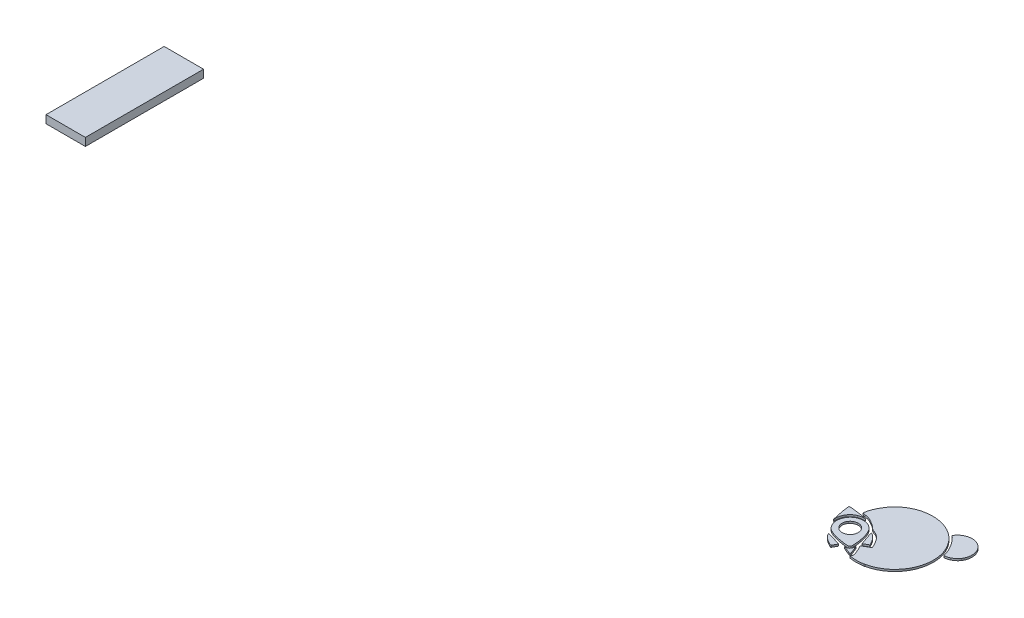
SolidWorks part; units mm, degrees
ref_plane "Alzado" through (0, 0, 0) normal (0, 0, 1) x (1, 0, 0)
ref_plane "Planta" through (0, 0, 0) normal (0, 1, 0) x (1, 0, 0)
ref_plane "Vista lateral" through (0, 0, 0) normal (1, 0, 0) x (0, 0, -1)
sketch "Croquis2" plane through (0, 0, 0) normal (0, 1, 0) x (1, 0, 0)
  line L1 (-10.1434, 10.8277) -> (39.8566, 10.8277)
  line L2 (-10.1434, 10.8277) -> (-10.1434, -4.1723)
  line L3 (-10.1434, -4.1723) -> (39.8566, -4.1723)
  line L4 (39.8566, 10.8277) -> (39.8566, -4.1723)
  line L5 (-10.1434, 10.8277) -> (39.8566, -4.1723) construction
  line L6 (-10.1434, -4.1723) -> (39.8566, 10.8277) construction
  point P0 (14.8566, 3.3277)
  dimension "D1" = 50
  dimension "D2" = 15
sketch "Croquis1" plane through (0, 0, 0) normal (0, 1, 0) x (1, 0, 0)
  line L0 (3.5784, 3.9291) -> (1.8314, 3.9291)
  line L1 (3.9335, 5.4773) -> (5.155, 5.4773)
  line L2 (5.155, 5.4773) -> (5.155, 2.4804)
  line L3 (5.155, 2.4804) -> (5.1692, 2.4804)
  line L4 (3.0387, 4.4262) -> (4.0755, 4.4262)
  line L5 (4.0755, 4.4262) -> (4.0755, -0.829)
  line L6 (4.0755, -0.829) -> (4.0755, -2.0789)
  line L7 (4.2602, -2.5051) -> (4.6579, -2.5051)
  line L8 (4.6579, -2.5051) -> (4.6579, 4.9802)
  line L9 (4.6579, 4.9802) -> (3.9193, 4.9802)
  line L10 (3.9193, 4.9802) -> (3.5926, 4.9716)
  line L11 (3.5926, 4.9716) -> (3.408, 4.8097)
  line L12 (3.408, 4.8097) -> (3.0387, 4.4262)
  line L13 (18.6341, 4.8097) -> (18.6341, 0.7333)
  line L14 (20.0828, -2.3346) -> (20.0828, -1.9369)
  line L15 (19.2164, -0.7154) -> (19.2164, 2.8781)
  line L16 (19.2164, 2.8781) -> (20.0828, 2.8781)
  line L17 (20.0828, 2.8781) -> (20.0828, 3.2758)
  line L18 (20.0828, 3.2758) -> (20.0682, 3.4234)
  line L19 (20.0682, 3.4234) -> (19.8556, 3.4462)
  line L20 (19.8556, 3.4462) -> (19.2164, 3.4462)
  line L21 (19.2164, 3.4462) -> (19.2164, 4.8097)
  line L22 (19.2164, 4.8097) -> (18.6341, 4.8097)
  line L23 (23.8893, 4.8097) -> (23.8893, 0.8044)
  line L24 (25.3239, -2.505) -> (25.3239, -1.9369)
  line L25 (24.4717, -0.7296) -> (24.4717, 2.8781)
  line L26 (24.4717, 2.8781) -> (25.3239, 2.8781)
  line L27 (25.3239, 2.8781) -> (25.3239, 3.4462)
  line L28 (25.3239, 3.4462) -> (24.4717, 3.4462)
  line L29 (24.4717, 3.4462) -> (24.4717, 4.8097)
  line L30 (24.4717, 4.8097) -> (23.8893, 4.8097)
  line L31 (-5.0999, 1.3015) -> (-5.0857, 1.3015)
  line L32 (5.5953, -2.505) -> (6.1634, -2.505)
  line L33 (7.74, -2.505) -> (8.3082, -2.505)
  line L34 (8.3082, -2.505) -> (8.3082, 1.5856)
  line L35 (5.5953, 0.6765) -> (5.5953, -2.505)
  line L36 (12.8249, 0.0267) -> (13.9469, 0.5878)
  line L37 (11.7312, 1.4009) -> (11.7312, -0.3177)
  line L38 (14.2736, -0.7296) -> (13.8759, -0.7296)
  line L39 (17.2989, -2.505) -> (17.725, -2.505)
  line L40 (17.8813, -2.0789) -> (17.8813, -1.0989)
  line L41 (15.1542, 1.2731) -> (15.1542, -0.7864)
  line L42 (15.1542, -0.7864) -> (15.1542, -2.0647)
  line L43 (15.7365, -2.2494) -> (15.7365, -1.525)
  line L44 (15.7365, -1.525) -> (15.7365, 1.1026)
  line L45 (17.2989, 1.1737) -> (17.2989, -0.3035)
  line L46 (17.2989, -0.3035) -> (17.2989, -2.505)
  line L47 (20.4521, 1.2447) -> (20.4521, -0.3319)
  line L48 (28.4202, -0.7296) -> (27.8521, -0.7296)
  line L49 (26.7868, 0.0197) -> (27.8379, 0.5452)
  line L50 (28.4202, 0.989) -> (28.4202, 1.4577)
  line L51 (25.7074, 1.3015) -> (25.7074, -0.6444)
  line L52 (31.687, -0.7864) -> (31.1189, -0.7864)
  line L53 (29.6559, -0.687) -> (29.6559, 1.3583)
  line L54 (31.1189, 1.7276) -> (31.687, 1.7276)
  line L55 (29.0878, 1.6992) -> (29.0878, -0.5876)
  line L56 (34.4851, -2.2352) -> (34.4851, -2.505)
  line L57 (34.4851, -2.505) -> (35.0248, -2.505)
  line L58 (35.0248, -2.505) -> (35.0248, 0.0658)
  line L59 (35.0248, 0.0658) -> (35.0248, 1.8696)
  line L60 (32.312, 1.5288) -> (32.312, -0.4029)
  line L61 (8.6632, 3.4462) -> (8.7709, 2.8213)
  line L62 (8.7709, 2.8213) -> (9.0496, 1.3583)
  line L63 (9.0496, 1.3583) -> (9.7853, -2.505)
  line L64 (10.5409, -1.1415) -> (11.1318, 1.9122)
  line L65 (11.4187, 3.4462) -> (10.8506, 3.4462)
  line L66 (10.041, -0.9853) -> (10.0268, -0.9853)
  line L67 (10.0268, -0.9853) -> (9.2456, 3.4462)
  line L68 (9.2456, 3.4462) -> (8.6632, 3.4462)
  line L69 (-0.2279, 2.4094) -> (-0.0054, 1.685)
  line L70 (-0.0054, 1.685) -> (0.5106, 0.1936)
  line L71 (0.5106, 0.1936) -> (1.306, 0.6481)
  line L72 (-0.4694, -1.5818) -> (-0.4694, -1.596)
  line L73 (-1.7335, -2.5051) -> (-1.3074, -1.6955)
  spline S0 degree 3 poles (8.6064, 5.0654) (8.9077, 5.0656) (9.231, 5.1421) (9.5012, 5.275) knots 0 0 0 0 1 1 1 1
  spline S1 degree 3 poles (9.5012, 5.275) (9.8765, 5.4595) (10.2057, 5.7212) (10.4375, 6.0738) knots 0 0 0 0 1 1 1 1
  spline S2 degree 3 poles (10.4375, 6.0738) (11.1456, 7.1512) (10.8182, 8.6685) (9.6859, 9.3162) knots 0 0 0 0 1 1 1 1
  spline S3 degree 3 poles (9.6859, 9.3162) (9.4504, 9.4509) (9.1882, 9.5508) (8.9189, 9.5924) knots 0 0 0 0 1 1 1 1
  spline S4 degree 3 poles (8.9189, 9.5924) (8.2132, 9.7014) (7.5188, 9.4932) (6.9872, 9.0163) knots 0 0 0 0 1 1 1 1
  spline S5 degree 3 poles (6.9872, 9.0163) (6.8569, 8.8994) (6.7378, 8.7633) (6.642, 8.6163) knots 0 0 0 0 1 1 1 1
  spline S6 degree 3 poles (6.642, 8.6163) (6.6153, 8.5752) (6.5511, 8.5009) (6.5671, 8.4482) knots 0 0 0 0 1 1 1 1
  spline S7 degree 3 poles (6.5671, 8.4482) (6.5982, 8.3461) (6.7844, 8.2366) (6.8594, 8.1618) knots 0 0 0 0 1 1 1 1
  spline S8 degree 3 poles (6.8594, 8.1618) (7.0821, 7.9394) (7.2857, 7.7003) (7.4783, 7.4516) knots 0 0 0 0 1 1 1 1
  spline S9 degree 3 poles (7.4783, 7.4516) (8.0092, 6.7663) (8.4305, 5.9176) (8.6064, 5.0654) knots 0 0 0 0 1 1 1 1
  spline S10 degree 3 poles (1.249, -2.4482) (1.8259, -2.5553) (2.4283, -2.5697) (3.0103, -2.5074) knots 0 0 0 0 1 1 1 1
  spline S11 degree 3 poles (3.0103, -2.5074) (3.1485, -2.4926) (3.2849, -2.4771) (3.4222, -2.4541) knots 0 0 0 0 1 1 1 1
  spline S12 degree 3 poles (3.4222, -2.4541) (3.4634, -2.4472) (3.536, -2.4479) (3.5638, -2.4115) knots 0 0 0 0 1 1 1 1
  spline S13 degree 3 poles (3.5638, -2.4115) (3.6258, -2.3302) (3.5784, -2.0665) (3.5784, -1.9653) knots 0 0 0 0 1 1 1 1
  spline S14 degree 3 poles (3.5784, -1.9653) (3.5784, -1.5582) (3.5826, -1.1506) (3.5785, -0.7438) knots 0 0 0 0 1 1 1 1
  spline S15 degree 3 poles (3.5785, -0.7438) (3.5624, 0.8135) (3.5784, 2.3718) (3.5784, 3.9291) knots 0 0 0 0 1 1 1 1
  spline S16 degree 3 poles (1.8314, 3.9291) (2.196, 4.2937) (2.5619, 4.657) (2.9251, 5.0228) knots 0 0 0 0 1 1 1 1
  spline S17 degree 3 poles (2.9251, 5.0228) (3.0505, 5.1491) (3.2259, 5.4068) (3.3938, 5.4687) knots 0 0 0 0 1 1 1 1
  spline S18 degree 3 poles (3.3938, 5.4687) (3.5397, 5.5225) (3.7781, 5.4773) (3.9335, 5.4773) knots 0 0 0 0 1 1 1 1
  spline S19 degree 3 poles (5.1692, 2.4804) (5.1849, 2.6775) (5.2637, 2.8864) (5.3504, 3.0627) knots 0 0 0 0 1 1 1 1
  spline S20 degree 3 poles (5.3504, 3.0627) (5.4291, 3.2228) (5.5273, 3.3749) (5.6523, 3.503) knots 0 0 0 0 1 1 1 1
  spline S21 degree 3 poles (5.6523, 3.503) (6.1635, 4.0269) (6.9766, 4.092) (7.669, 4.0261) knots 0 0 0 0 1 1 1 1
  spline S22 degree 3 poles (7.669, 4.0261) (7.9276, 4.0015) (8.1757, 3.9433) (8.436, 3.9433) knots 0 0 0 0 1 1 1 1
  spline S23 degree 3 poles (8.436, 3.9433) (8.4211, 4.6648) (8.1948, 5.4069) (7.9006, 6.0596) knots 0 0 0 0 1 1 1 1
  spline S24 degree 3 poles (7.9006, 6.0596) (7.6039, 6.7178) (7.1847, 7.3109) (6.6748, 7.8209) knots 0 0 0 0 1 1 1 1
  spline S25 degree 3 poles (6.6748, 7.8209) (4.3405, 10.1551) (0.3296, 10.1882) (-1.9888, 7.7924) knots 0 0 0 0 1 1 1 1
  spline S26 degree 3 poles (-1.9888, 7.7924) (-2.5824, 7.179) (-3.048, 6.4468) (-3.3469, 5.6477) knots 0 0 0 0 1 1 1 1
  spline S27 degree 3 poles (-3.3469, 5.6477) (-3.4496, 5.373) (-3.5439, 5.0853) (-3.5932, 4.7955) knots 0 0 0 0 1 1 1 1
  spline S28 degree 3 poles (-3.5932, 4.7955) (-3.6044, 4.7295) (-3.6663, 4.5655) (-3.6223, 4.5076) knots 0 0 0 0 1 1 1 1
  spline S29 degree 3 poles (-3.6223, 4.5076) (-3.5662, 4.4338) (-3.3265, 4.4339) (-3.2393, 4.4176) knots 0 0 0 0 1 1 1 1
  spline S30 degree 3 poles (-3.2393, 4.4176) (-2.9214, 4.358) (-2.5794, 4.305) (-2.2876, 4.1591) knots 0 0 0 0 1 1 1 1
  spline S31 degree 3 poles (-2.2876, 4.1591) (-1.8381, 3.9343) (-1.3834, 3.6639) (-0.9809, 3.3625) knots 0 0 0 0 1 1 1 1
  spline S32 degree 3 poles (-0.9809, 3.3625) (-0.8218, 3.2433) (-0.7083, 3.076) (-0.5406, 2.9695) knots 0 0 0 0 1 1 1 1
  spline S33 degree 3 poles (-0.5406, 2.9695) (-0.3336, 2.8379) (-0.0782, 2.7996) (0.1412, 2.6899) knots 0 0 0 0 1 1 1 1
  spline S34 degree 3 poles (0.1412, 2.6899) (0.5113, 2.5048) (0.836, 2.1978) (1.0843, 1.8696) knots 0 0 0 0 1 1 1 1
  spline S35 degree 3 poles (1.0843, 1.8696) (1.33, 1.5449) (1.5407, 1.1895) (1.7079, 0.8186) knots 0 0 0 0 1 1 1 1
  spline S36 degree 3 poles (1.7079, 0.8186) (1.7431, 0.7404) (1.8858, 0.5189) (1.8243, 0.4405) knots 0 0 0 0 1 1 1 1
  spline S37 degree 3 poles (1.8243, 0.4405) (1.7648, 0.3647) (1.63, 0.3142) (1.5473, 0.2668) knots 0 0 0 0 1 1 1 1
  spline S38 degree 3 poles (1.5473, 0.2668) (1.3568, 0.1574) (1.1682, 0.0444) (0.9792, -0.0677) knots 0 0 0 0 1 1 1 1
  spline S39 degree 3 poles (0.9792, -0.0677) (0.9056, -0.1113) (0.7125, -0.1778) (0.7026, -0.2753) knots 0 0 0 0 1 1 1 1
  spline S40 degree 3 poles (0.7026, -0.2753) (0.6938, -0.3635) (0.7928, -0.4849) (0.8328, -0.5592) knots 0 0 0 0 1 1 1 1
  spline S41 degree 3 poles (0.8328, -0.5592) (0.9419, -0.7624) (1.0292, -0.9842) (1.1148, -1.1983) knots 0 0 0 0 1 1 1 1
  spline S42 degree 3 poles (1.1148, -1.1983) (1.2129, -1.4436) (1.3946, -1.782) (1.3874, -2.0505) knots 0 0 0 0 1 1 1 1
  spline S43 degree 3 poles (1.3874, -2.0505) (1.3833, -2.2048) (1.2596, -2.3074) (1.249, -2.4482) knots 0 0 0 0 1 1 1 1
  spline S44 degree 3 poles (4.0755, -2.0789) (4.0755, -2.1593) (4.0324, -2.4382) (4.0983, -2.4904) knots 0 0 0 0 1 1 1 1
  spline S45 degree 3 poles (4.0983, -2.4904) (4.1355, -2.5199) (4.2158, -2.5051) (4.2602, -2.5051) knots 0 0 0 0 1 1 1 1
  spline S46 degree 3 poles (18.6341, 0.7333) (18.6341, 0.0083) (18.5456, -0.7838) (18.6909, -1.4966) knots 0 0 0 0 1 1 1 1
  spline S47 degree 3 poles (18.6909, -1.4966) (18.793, -1.9969) (19.1188, -2.3957) (19.6425, -2.4747) knots 0 0 0 0 1 1 1 1
  spline S48 degree 3 poles (19.6425, -2.4747) (19.7238, -2.487) (20.0105, -2.5551) (20.0682, -2.4823) knots 0 0 0 0 1 1 1 1
  spline S49 degree 3 poles (20.0682, -2.4823) (20.0957, -2.4475) (20.0828, -2.3759) (20.0828, -2.3346) knots 0 0 0 0 1 1 1 1
  spline S50 degree 3 poles (20.0828, -1.9369) (19.9348, -1.9369) (19.7843, -1.944) (19.6425, -1.893) knots 0 0 0 0 1 1 1 1
  spline S51 degree 3 poles (19.6425, -1.893) (19.1744, -1.7245) (19.2164, -1.1155) (19.2164, -0.7154) knots 0 0 0 0 1 1 1 1
  spline S52 degree 3 poles (23.8893, 0.8044) (23.8893, 0.0865) (23.8209, -0.6716) (23.9219, -1.383) knots 0 0 0 0 1 1 1 1
  spline S53 degree 3 poles (23.9219, -1.383) (23.9774, -1.7751) (24.1589, -2.173) (24.5285, -2.3577) knots 0 0 0 0 1 1 1 1
  spline S54 degree 3 poles (24.5285, -2.3577) (24.7735, -2.4803) (25.0542, -2.505) (25.3239, -2.505) knots 0 0 0 0 1 1 1 1
  spline S55 degree 3 poles (25.3239, -1.9369) (25.1804, -1.9369) (25.0351, -1.9424) (24.8978, -1.893) knots 0 0 0 0 1 1 1 1
  spline S56 degree 3 poles (24.8978, -1.893) (24.4304, -1.7248) (24.4717, -1.1296) (24.4717, -0.7296) knots 0 0 0 0 1 1 1 1
  spline S57 degree 3 poles (-5.0857, 1.3015) (-5.2118, 2.2995) (-4.6942, 3.2922) (-3.7506, 3.6958) knots 0 0 0 0 1 1 1 1
  spline S58 degree 3 poles (-3.7506, 3.6958) (-3.393, 3.8487) (-3.0397, 3.8723) (-2.6569, 3.8723) knots 0 0 0 0 1 1 1 1
  spline S59 degree 3 poles (-2.6569, 3.8723) (-2.8408, 3.9708) (-3.1066, 3.9878) (-3.3103, 4.0285) knots 0 0 0 0 1 1 1 1
  spline S60 degree 3 poles (-3.3103, 4.0285) (-3.8355, 4.1336) (-4.3684, 4.2018) (-4.9011, 4.2534) knots 0 0 0 0 1 1 1 1
  spline S61 degree 3 poles (-4.9011, 4.2534) (-5.0712, 4.2699) (-5.2428, 4.2744) (-5.4124, 4.2944) knots 0 0 0 0 1 1 1 1
  spline S62 degree 3 poles (-5.4124, 4.2944) (-5.4785, 4.3021) (-5.5696, 4.3043) (-5.6087, 4.2386) knots 0 0 0 0 1 1 1 1
  spline S63 degree 3 poles (-5.6087, 4.2386) (-5.6475, 4.1732) (-5.6211, 4.0706) (-5.6136, 4.0001) knots 0 0 0 0 1 1 1 1
  spline S64 degree 3 poles (-5.6136, 4.0001) (-5.5938, 3.8152) (-5.5734, 3.6303) (-5.5462, 3.4462) knots 0 0 0 0 1 1 1 1
  spline S65 degree 3 poles (-5.5462, 3.4462) (-5.4383, 2.7175) (-5.2486, 2.0198) (-5.0999, 1.3015) knots 0 0 0 0 1 1 1 1
  spline S66 degree 3 poles (6.1634, -2.505) (6.1634, -1.0898) (6.1467, 0.3266) (6.1635, 1.7418) knots 0 0 0 0 1 1 1 1
  spline S67 degree 3 poles (6.1635, 1.7418) (6.169, 2.2046) (6.2911, 2.9193) (6.8736, 2.962) knots 0 0 0 0 1 1 1 1
  spline S68 degree 3 poles (6.8736, 2.962) (7.5002, 3.0079) (7.7269, 2.3808) (7.7398, 1.8554) knots 0 0 0 0 1 1 1 1
  spline S69 degree 3 poles (7.7398, 1.8554) (7.7754, 0.4039) (7.74, -1.053) (7.74, -2.505) knots 0 0 0 0 1 1 1 1
  spline S70 degree 3 poles (8.3082, 1.5856) (8.3082, 2.1988) (8.2853, 2.9291) (7.7258, 3.3178) knots 0 0 0 0 1 1 1 1
  spline S71 degree 3 poles (7.7258, 3.3178) (6.9874, 3.8309) (5.9192, 3.4358) (5.6931, 2.5798) knots 0 0 0 0 1 1 1 1
  spline S72 degree 3 poles (5.6931, 2.5798) (5.5313, 1.9677) (5.5953, 1.3043) (5.5953, 0.6765) knots 0 0 0 0 1 1 1 1
  spline S73 degree 3 poles (13.8759, -0.7296) (13.8759, -1.0655) (13.8736, -1.4161) (13.6835, -1.7096) knots 0 0 0 0 1 1 1 1
  spline S74 degree 3 poles (13.6835, -1.7096) (13.4417, -2.0828) (12.9078, -2.1527) (12.5989, -1.8232) knots 0 0 0 0 1 1 1 1
  spline S75 degree 3 poles (12.5989, -1.8232) (12.4436, -1.6576) (12.3743, -1.4322) (12.3384, -1.2125) knots 0 0 0 0 1 1 1 1
  spline S76 degree 3 poles (12.3384, -1.2125) (12.3002, -0.9785) (12.3135, -0.7388) (12.3135, -0.5024) knots 0 0 0 0 1 1 1 1
  spline S77 degree 3 poles (12.3135, -0.5024) (12.3135, -0.431) (12.2885, -0.3001) (12.3282, -0.238) knots 0 0 0 0 1 1 1 1
  spline S78 degree 3 poles (12.3282, -0.238) (12.4037, -0.1195) (12.6997, -0.0359) (12.8249, 0.0267) knots 0 0 0 0 1 1 1 1
  spline S79 degree 3 poles (13.9469, 0.5878) (14.0847, 0.6567) (14.3335, 0.7261) (14.4355, 0.8418) knots 0 0 0 0 1 1 1 1
  spline S80 degree 3 poles (14.4355, 0.8418) (14.5115, 0.928) (14.4583, 1.2316) (14.4583, 1.3441) knots 0 0 0 0 1 1 1 1
  spline S81 degree 3 poles (14.4583, 1.3441) (14.4583, 1.8539) (14.4759, 2.3949) (14.2414, 2.8639) knots 0 0 0 0 1 1 1 1
  spline S82 degree 3 poles (14.2414, 2.8639) (13.8167, 3.7132) (12.4813, 3.7693) (11.9932, 2.9491) knots 0 0 0 0 1 1 1 1
  spline S83 degree 3 poles (11.9932, 2.9491) (11.7168, 2.4845) (11.7312, 1.922) (11.7312, 1.4009) knots 0 0 0 0 1 1 1 1
  spline S84 degree 3 poles (11.7312, -0.3177) (11.7312, -0.7614) (11.7137, -1.2075) (11.8367, -1.6386) knots 0 0 0 0 1 1 1 1
  spline S85 degree 3 poles (11.8367, -1.6386) (12.0444, -2.3666) (12.7389, -2.7261) (13.464, -2.5491) knots 0 0 0 0 1 1 1 1
  spline S86 degree 3 poles (13.464, -2.5491) (14.0706, -2.401) (14.363, -1.8326) (14.4321, -1.2551) knots 0 0 0 0 1 1 1 1
  spline S87 degree 3 poles (14.4321, -1.2551) (14.4472, -1.1283) (14.4583, -0.9994) (14.4583, -0.8716) knots 0 0 0 0 1 1 1 1
  spline S88 degree 3 poles (14.4583, -0.8716) (14.4583, -0.8345) (14.4689, -0.7707) (14.4355, -0.7442) knots 0 0 0 0 1 1 1 1
  spline S89 degree 3 poles (14.4355, -0.7442) (14.3983, -0.7148) (14.3179, -0.7296) (14.2736, -0.7296) knots 0 0 0 0 1 1 1 1
  spline S90 degree 3 poles (17.725, -2.505) (17.7682, -2.505) (17.8493, -2.5197) (17.8728, -2.4721) knots 0 0 0 0 1 1 1 1
  spline S91 degree 3 poles (17.8728, -2.4721) (17.9191, -2.3779) (17.8813, -2.1835) (17.8813, -2.0789) knots 0 0 0 0 1 1 1 1
  spline S92 degree 3 poles (17.8813, -1.0989) (17.8813, -0.0732) (17.9125, 0.9594) (17.8676, 1.9833) knots 0 0 0 0 1 1 1 1
  spline S93 degree 3 poles (17.8676, 1.9833) (17.846, 2.4772) (17.7168, 3.0451) (17.2705, 3.3313) knots 0 0 0 0 1 1 1 1
  spline S94 degree 3 poles (17.2705, 3.3313) (16.5801, 3.7741) (15.5934, 3.4929) (15.3023, 2.7218) knots 0 0 0 0 1 1 1 1
  spline S95 degree 3 poles (15.3023, 2.7218) (15.1284, 2.2611) (15.1542, 1.7567) (15.1542, 1.2731) knots 0 0 0 0 1 1 1 1
  spline S96 degree 3 poles (15.1542, -2.0647) (15.1542, -2.1471) (15.1097, -2.4372) (15.1769, -2.4904) knots 0 0 0 0 1 1 1 1
  spline S97 degree 3 poles (15.1769, -2.4904) (15.2274, -2.5303) (15.3627, -2.505) (15.4241, -2.505) knots 0 0 0 0 1 1 1 1
  spline S98 degree 3 poles (15.4241, -2.505) (15.4937, -2.505) (15.6573, -2.5352) (15.7138, -2.4904) knots 0 0 0 0 1 1 1 1
  spline S99 degree 3 poles (15.7138, -2.4904) (15.7625, -2.4518) (15.7365, -2.3053) (15.7365, -2.2494) knots 0 0 0 0 1 1 1 1
  spline S100 degree 3 poles (15.7365, 1.1026) (15.7365, 1.5661) (15.6716, 2.0888) (15.8688, 2.523) knots 0 0 0 0 1 1 1 1
  spline S101 degree 3 poles (15.8688, 2.523) (16.1063, 3.0459) (16.8034, 3.1218) (17.1133, 2.6224) knots 0 0 0 0 1 1 1 1
  spline S102 degree 3 poles (17.1133, 2.6224) (17.3724, 2.2051) (17.2989, 1.6412) (17.2989, 1.1737) knots 0 0 0 0 1 1 1 1
  spline S103 degree 3 poles (21.6736, 3.5254) (21.1756, 3.4592) (20.7933, 3.2202) (20.6056, 2.736) knots 0 0 0 0 1 1 1 1
  spline S104 degree 3 poles (20.6056, 2.736) (20.4224, 2.2629) (20.4521, 1.7424) (20.4521, 1.2447) knots 0 0 0 0 1 1 1 1
  spline S105 degree 3 poles (20.4521, -0.3319) (20.4521, -0.7523) (20.4386, -1.1711) (20.5426, -1.5818) knots 0 0 0 0 1 1 1 1
  spline S106 degree 3 poles (20.5426, -1.5818) (20.7266, -2.3081) (21.3444, -2.6751) (22.0713, -2.572) knots 0 0 0 0 1 1 1 1
  spline S107 degree 3 poles (22.0713, -2.572) (22.632, -2.4925) (22.9742, -2.0485) (23.1029, -1.525) knots 0 0 0 0 1 1 1 1
  spline S108 degree 3 poles (23.1029, -1.525) (23.2759, -0.8203) (23.1792, -0.0161) (23.1792, 0.705) knots 0 0 0 0 1 1 1 1
  spline S109 degree 3 poles (23.1792, 0.705) (23.1792, 1.3385) (23.2571, 2.0402) (23.056, 2.6508) knots 0 0 0 0 1 1 1 1
  spline S110 degree 3 poles (23.056, 2.6508) (22.8601, 3.2453) (22.3012, 3.6088) (21.6736, 3.5254) knots 0 0 0 0 1 1 1 1
  spline S111 degree 3 poles (27.8521, -0.7296) (27.8521, -1.0649) (27.8467, -1.4176) (27.6575, -1.7096) knots 0 0 0 0 1 1 1 1
  spline S112 degree 3 poles (27.6575, -1.7096) (27.395, -2.115) (26.8232, -2.1464) (26.5244, -1.7665) knots 0 0 0 0 1 1 1 1
  spline S113 degree 3 poles (26.5244, -1.7665) (26.2184, -1.3775) (26.2866, -0.7937) (26.2897, -0.3319) knots 0 0 0 0 1 1 1 1
  spline S114 degree 3 poles (26.2897, -0.3319) (26.291, -0.1431) (26.6374, -0.055) (26.7868, 0.0197) knots 0 0 0 0 1 1 1 1
  spline S115 degree 3 poles (27.8379, 0.5452) (28.0134, 0.633) (28.2117, 0.7076) (28.3755, 0.8157) knots 0 0 0 0 1 1 1 1
  spline S116 degree 3 poles (28.3755, 0.8157) (28.4344, 0.8546) (28.4202, 0.9268) (28.4202, 0.989) knots 0 0 0 0 1 1 1 1
  spline S117 degree 3 poles (28.4202, 1.4577) (28.4202, 2.1038) (28.4332, 2.8943) (27.8379, 3.3121) knots 0 0 0 0 1 1 1 1
  spline S118 degree 3 poles (27.8379, 3.3121) (27.4055, 3.6156) (26.7003, 3.6153) (26.2755, 3.2969) knots 0 0 0 0 1 1 1 1
  spline S119 degree 3 poles (26.2755, 3.2969) (26.0635, 3.1379) (25.9265, 2.9118) (25.8383, 2.665) knots 0 0 0 0 1 1 1 1
  spline S120 degree 3 poles (25.8383, 2.665) (25.6821, 2.2279) (25.7074, 1.7578) (25.7074, 1.3015) knots 0 0 0 0 1 1 1 1
  spline S121 degree 3 poles (25.7074, -0.6444) (25.7074, -1.134) (25.7268, -1.6575) (26.0108, -2.0789) knots 0 0 0 0 1 1 1 1
  spline S122 degree 3 poles (26.0108, -2.0789) (26.4425, -2.7199) (27.5261, -2.7746) (28.0326, -2.1926) knots 0 0 0 0 1 1 1 1
  spline S123 degree 3 poles (28.0326, -2.1926) (28.3857, -1.7868) (28.4307, -1.2407) (28.4202, -0.7296) knots 0 0 0 0 1 1 1 1
  spline S124 degree 3 poles (31.1189, -0.7864) (31.1189, -1.0988) (31.1247, -1.4528) (30.9433, -1.7238) knots 0 0 0 0 1 1 1 1
  spline S125 degree 3 poles (30.9433, -1.7238) (30.6722, -2.129) (30.0842, -2.1175) (29.8221, -1.7096) knots 0 0 0 0 1 1 1 1
  spline S126 degree 3 poles (29.8221, -1.7096) (29.6349, -1.4183) (29.6559, -1.0185) (29.6559, -0.687) knots 0 0 0 0 1 1 1 1
  spline S127 degree 3 poles (29.6559, 1.3583) (29.6559, 1.7297) (29.6099, 2.157) (29.7534, 2.5088) knots 0 0 0 0 1 1 1 1
  spline S128 degree 3 poles (29.7534, 2.5088) (29.9487, 2.9872) (30.5759, 3.1426) (30.9125, 2.7076) knots 0 0 0 0 1 1 1 1
  spline S129 degree 3 poles (30.9125, 2.7076) (31.1239, 2.4346) (31.1189, 2.0549) (31.1189, 1.7276) knots 0 0 0 0 1 1 1 1
  spline S130 degree 3 poles (31.687, 1.7276) (31.687, 2.2245) (31.6629, 2.7337) (31.3257, 3.1337) knots 0 0 0 0 1 1 1 1
  spline S131 degree 3 poles (31.3257, 3.1337) (30.8391, 3.7111) (29.7916, 3.6561) (29.3683, 3.0343) knots 0 0 0 0 1 1 1 1
  spline S132 degree 3 poles (29.3683, 3.0343) (29.0996, 2.6396) (29.0878, 2.1582) (29.0878, 1.6992) knots 0 0 0 0 1 1 1 1
  spline S133 degree 3 poles (29.0878, -0.5876) (29.0878, -1.0915) (29.0672, -1.6212) (29.3497, -2.0647) knots 0 0 0 0 1 1 1 1
  spline S134 degree 3 poles (29.3497, -2.0647) (29.7671, -2.7203) (30.8463, -2.7798) (31.3396, -2.1784) knots 0 0 0 0 1 1 1 1
  spline S135 degree 3 poles (31.3396, -2.1784) (31.6657, -1.7805) (31.687, -1.2751) (31.687, -0.7864) knots 0 0 0 0 1 1 1 1
  spline S136 degree 3 poles (35.0248, 1.8696) (35.0248, 2.3295) (34.9257, 2.8674) (34.5821, 3.2007) knots 0 0 0 0 1 1 1 1
  spline S137 degree 3 poles (34.5821, 3.2007) (34.04, 3.7265) (32.9734, 3.6293) (32.5763, 2.9775) knots 0 0 0 0 1 1 1 1
  spline S138 degree 3 poles (32.5763, 2.9775) (32.3087, 2.5382) (32.312, 2.025) (32.312, 1.5288) knots 0 0 0 0 1 1 1 1
  spline S139 degree 3 poles (32.312, -0.4029) (32.312, -0.8505) (32.2849, -1.3096) (32.4405, -1.738) knots 0 0 0 0 1 1 1 1
  spline S140 degree 3 poles (32.4405, -1.738) (32.5287, -1.9806) (32.67, -2.209) (32.8801, -2.3641) knots 0 0 0 0 1 1 1 1
  spline S141 degree 3 poles (32.8801, -2.3641) (33.3618, -2.7195) (34.0705, -2.6495) (34.4851, -2.2352) knots 0 0 0 0 1 1 1 1
  spline S142 degree 3 poles (-2.7989, 3.4828) (-3.1486, 3.4363) (-3.4873, 3.3276) (-3.779, 3.1235) knots 0 0 0 0 1 1 1 1
  spline S143 degree 3 poles (-3.779, 3.1235) (-4.7667, 2.4324) (-4.984, 1.0203) (-4.2493, 0.0658) knots 0 0 0 0 1 1 1 1
  spline S144 degree 3 poles (-4.2493, 0.0658) (-3.8559, -0.4453) (-3.2576, -0.6681) (-2.6569, -0.8351) knots 0 0 0 0 1 1 1 1
  spline S145 degree 3 poles (-2.6569, -0.8351) (-2.186, -0.966) (-1.7081, -1.0714) (-1.2224, -1.1295) knots 0 0 0 0 1 1 1 1
  spline S146 degree 3 poles (-1.2224, -1.1295) (-0.9209, -1.1656) (-0.5431, -1.2464) (-0.2423, -1.1936) knots 0 0 0 0 1 1 1 1
  spline S147 degree 3 poles (-0.2423, -1.1936) (0.0019, -1.1508) (-0.0009, -0.9264) (-0.0009, -0.7296) knots 0 0 0 0 1 1 1 1
  spline S148 degree 3 poles (-0.0009, -0.7296) (-0.0009, -0.2796) (-0.0544, 0.1771) (-0.1374, 0.6197) knots 0 0 0 0 1 1 1 1
  spline S149 degree 3 poles (-0.1374, 0.6197) (-0.3277, 1.6352) (-0.6234, 2.7969) (-1.6343, 3.2863) knots 0 0 0 0 1 1 1 1
  spline S150 degree 3 poles (-1.6343, 3.2863) (-1.8009, 3.367) (-1.9786, 3.4216) (-2.1598, 3.4576) knots 0 0 0 0 1 1 1 1
  spline S151 degree 3 poles (-2.1598, 3.4576) (-2.3616, 3.4976) (-2.5944, 3.51) (-2.7989, 3.4828) knots 0 0 0 0 1 1 1 1
  spline S152 degree 3 poles (9.7853, -2.505) (9.8924, -2.505) (10.1743, -2.5557) (10.2599, -2.4904) knots 0 0 0 0 1 1 1 1
  spline S153 degree 3 poles (10.2599, -2.4904) (10.3266, -2.4396) (10.3317, -2.2158) (10.3478, -2.1357) knots 0 0 0 0 1 1 1 1
  spline S154 degree 3 poles (10.3478, -2.1357) (10.4138, -1.8047) (10.477, -1.473) (10.5409, -1.1415) knots 0 0 0 0 1 1 1 1
  spline S155 degree 3 poles (11.1318, 1.9122) (11.194, 2.2342) (11.2559, 2.5563) (11.3193, 2.8781) knots 0 0 0 0 1 1 1 1
  spline S156 degree 3 poles (11.3193, 2.8781) (11.3558, 3.0635) (11.4147, 3.2567) (11.4187, 3.4462) knots 0 0 0 0 1 1 1 1
  spline S157 degree 3 poles (10.8506, 3.4462) (10.658, 2.4534) (10.4702, 1.4588) (10.2907, 0.4635) knots 0 0 0 0 1 1 1 1
  spline S158 degree 3 poles (10.2907, 0.4635) (10.2062, -0.0049) (10.0423, -0.5084) (10.041, -0.9853) knots 0 0 0 0 1 1 1 1
  spline S159 degree 3 poles (12.3135, 0.4351) (12.3135, 0.9401) (12.2919, 1.4504) (12.3142, 1.9548) knots 0 0 0 0 1 1 1 1
  spline S160 degree 3 poles (12.3142, 1.9548) (12.3217, 2.1278) (12.3608, 2.3033) (12.4179, 2.4662) knots 0 0 0 0 1 1 1 1
  spline S161 degree 3 poles (12.4179, 2.4662) (12.5939, 2.9676) (13.2485, 3.1556) (13.6178, 2.736) knots 0 0 0 0 1 1 1 1
  spline S162 degree 3 poles (13.6178, 2.736) (13.8624, 2.4581) (13.876, 2.0347) (13.876, 1.685) knots 0 0 0 0 1 1 1 1
  spline S163 degree 3 poles (13.876, 1.685) (13.876, 1.5734) (13.9257, 1.3033) (13.8614, 1.2111) knots 0 0 0 0 1 1 1 1
  spline S164 degree 3 poles (13.8614, 1.2111) (13.7922, 1.112) (13.5574, 1.0463) (13.4499, 0.9925) knots 0 0 0 0 1 1 1 1
  spline S165 degree 3 poles (13.4499, 0.9925) (13.0887, 0.8119) (12.7012, 0.5467) (12.3135, 0.4351) knots 0 0 0 0 1 1 1 1
  spline S166 degree 3 poles (21.7021, 2.9592) (22.1935, 3.0232) (22.4782, 2.6546) (22.562, 2.2105) knots 0 0 0 0 1 1 1 1
  spline S167 degree 3 poles (22.562, 2.2105) (22.6598, 1.6913) (22.5969, 1.1183) (22.5969, 0.5913) knots 0 0 0 0 1 1 1 1
  spline S168 degree 3 poles (22.5969, 0.5913) (22.5969, 0.0555) (22.6608, -0.5254) (22.591, -1.0563) knots 0 0 0 0 1 1 1 1
  spline S169 degree 3 poles (22.591, -1.0563) (22.5357, -1.4759) (22.4111, -1.9678) (21.9152, -2.0322) knots 0 0 0 0 1 1 1 1
  spline S170 degree 3 poles (21.9152, -2.0322) (21.4322, -2.095) (21.1509, -1.7154) (21.0695, -1.2835) knots 0 0 0 0 1 1 1 1
  spline S171 degree 3 poles (21.0695, -1.2835) (20.974, -0.7776) (21.0345, -0.2205) (21.0345, 0.293) knots 0 0 0 0 1 1 1 1
  spline S172 degree 3 poles (21.0345, 0.293) (21.0345, 0.8494) (20.9732, 1.4453) (21.0387, 1.9975) knots 0 0 0 0 1 1 1 1
  spline S173 degree 3 poles (21.0387, 1.9975) (21.0868, 2.4044) (21.2242, 2.8969) (21.7021, 2.9592) knots 0 0 0 0 1 1 1 1
  spline S174 degree 3 poles (26.2898, 0.4351) (26.2898, 0.9495) (26.268, 1.4693) (26.2905, 1.9833) knots 0 0 0 0 1 1 1 1
  spline S175 degree 3 poles (26.2905, 1.9833) (26.2977, 2.1479) (26.3339, 2.3277) (26.3957, 2.4804) knots 0 0 0 0 1 1 1 1
  spline S176 degree 3 poles (26.3957, 2.4804) (26.5848, 2.947) (27.2097, 3.1662) (27.5799, 2.7502) knots 0 0 0 0 1 1 1 1
  spline S177 degree 3 poles (27.5799, 2.7502) (27.8277, 2.4716) (27.8523, 2.0525) (27.8523, 1.6992) knots 0 0 0 0 1 1 1 1
  spline S178 degree 3 poles (27.8523, 1.6992) (27.8523, 1.5847) (27.9037, 1.3056) (27.8377, 1.2111) knots 0 0 0 0 1 1 1 1
  spline S179 degree 3 poles (27.8377, 1.2111) (27.7685, 1.112) (27.5337, 1.0463) (27.4262, 0.9925) knots 0 0 0 0 1 1 1 1
  spline S180 degree 3 poles (27.4262, 0.9925) (27.065, 0.8119) (26.6775, 0.5467) (26.2898, 0.4351) knots 0 0 0 0 1 1 1 1
  spline S181 degree 3 poles (33.5479, 2.9592) (34.0622, 3.0262) (34.3477, 2.6316) (34.4222, 2.1679) knots 0 0 0 0 1 1 1 1
  spline S182 degree 3 poles (34.4222, 2.1679) (34.5004, 1.6824) (34.4569, 1.1672) (34.4569, 0.6765) knots 0 0 0 0 1 1 1 1
  spline S183 degree 3 poles (34.4569, 0.6765) (34.4569, 0.0893) (34.496, -0.5144) (34.4403, -1.0989) knots 0 0 0 0 1 1 1 1
  spline S184 degree 3 poles (34.4403, -1.0989) (34.4014, -1.5073) (34.2403, -1.9718) (33.7751, -2.0322) knots 0 0 0 0 1 1 1 1
  spline S185 degree 3 poles (33.7751, -2.0322) (33.2618, -2.0989) (32.9768, -1.687) (32.9106, -1.2267) knots 0 0 0 0 1 1 1 1
  spline S186 degree 3 poles (32.9106, -1.2267) (32.8431, -0.7573) (32.8803, -0.2658) (32.8803, 0.2078) knots 0 0 0 0 1 1 1 1
  spline S187 degree 3 poles (32.8803, 0.2078) (32.8803, 0.8165) (32.853, 1.4333) (32.8958, 2.0401) knots 0 0 0 0 1 1 1 1
  spline S188 degree 3 poles (32.8958, 2.0401) (32.9234, 2.4312) (33.109, 2.902) (33.5479, 2.9592) knots 0 0 0 0 1 1 1 1
  spline S189 degree 3 poles (-2.7277, 2.7036) (-2.5814, 2.7211) (-2.43, 2.7037) (-2.2874, 2.6699) knots 0 0 0 0 1 1 1 1
  spline S190 degree 3 poles (-2.2874, 2.6699) (-1.1935, 2.4111) (-0.9731, 0.8855) (-1.9323, 0.3137) knots 0 0 0 0 1 1 1 1
  spline S191 degree 3 poles (-1.9323, 0.3137) (-2.0844, 0.223) (-2.2536, 0.1625) (-2.4295, 0.1409) knots 0 0 0 0 1 1 1 1
  spline S192 degree 3 poles (-2.4295, 0.1409) (-3.5335, 0.0052) (-4.3235, 1.2936) (-3.6334, 2.1963) knots 0 0 0 0 1 1 1 1
  spline S193 degree 3 poles (-3.6334, 2.1963) (-3.5368, 2.3227) (-3.4182, 2.4341) (-3.2817, 2.5166) knots 0 0 0 0 1 1 1 1
  spline S194 degree 3 poles (-3.2817, 2.5166) (-3.1119, 2.6193) (-2.9245, 2.68) (-2.7277, 2.7036) knots 0 0 0 0 1 1 1 1
  spline S195 degree 3 poles (1.306, 0.6481) (1.0971, 1.15) (0.7734, 1.6633) (0.3686, 2.0283) knots 0 0 0 0 1 1 1 1
  spline S196 degree 3 poles (0.3686, 2.0283) (0.1962, 2.1837) (-0.0003, 2.3438) (-0.2279, 2.4094) knots 0 0 0 0 1 1 1 1
  spline S197 degree 3 poles (0.3828, -0.6586) (0.4278, -1.0147) (0.3325, -1.4031) (-0.0433, -1.5379) knots 0 0 0 0 1 1 1 1
  spline S198 degree 3 poles (-0.0433, -1.5379) (-0.1819, -1.5877) (-0.3247, -1.5818) (-0.4694, -1.5818) knots 0 0 0 0 1 1 1 1
  spline S199 degree 3 poles (-0.4694, -1.596) (-0.137, -1.7344) (0.1856, -1.8843) (0.5248, -2.0072) knots 0 0 0 0 1 1 1 1
  spline S200 degree 3 poles (0.5248, -2.0072) (0.6051, -2.0362) (0.8098, -2.1351) (0.8896, -2.0881) knots 0 0 0 0 1 1 1 1
  spline S201 degree 3 poles (0.8896, -2.0881) (0.9846, -2.0321) (0.8664, -1.797) (0.8421, -1.7239) knots 0 0 0 0 1 1 1 1
  spline S202 degree 3 poles (0.8421, -1.7239) (0.7551, -1.4631) (0.6526, -1.2057) (0.5359, -0.9569) knots 0 0 0 0 1 1 1 1
  spline S203 degree 3 poles (0.5359, -0.9569) (0.4895, -0.8579) (0.453, -0.7434) (0.3828, -0.6586) knots 0 0 0 0 1 1 1 1
  spline S204 degree 3 poles (-3.5657, -1.0421) (-3.3363, -1.5931) (-2.8179, -1.9576) (-2.3158, -2.2412) knots 0 0 0 0 1 1 1 1
  spline S205 degree 3 poles (-2.3158, -2.2412) (-2.1437, -2.3385) (-1.9309, -2.4755) (-1.7335, -2.5051) knots 0 0 0 0 1 1 1 1
  spline S206 degree 3 poles (-1.3074, -1.6955) (-1.5281, -1.6858) (-1.7654, -1.5685) (-1.975, -1.5015) knots 0 0 0 0 1 1 1 1
  spline S207 degree 3 poles (-1.975, -1.5015) (-2.4848, -1.3386) (-3.0358, -1.1201) (-3.5657, -1.0421) knots 0 0 0 0 1 1 1 1
extrude "Saliente-Extruir1" add sketch "Croquis1" along normal blind 0.3
sketch "Croquis3" plane through (0, 0.3, 0) normal (0, 1, 0) x (1, 0, 0)
  line L1 (36.2989, -3.7236) -> (3.9193, -3.7236)
  line L2 (36.2989, -3.7236) -> (36.2989, 4.9802)
  line L3 (36.2989, 4.9802) -> (3.9193, 4.9802)
  line L4 (3.9193, -3.7236) -> (3.9193, 4.9802)
extrude "Cortar-Extruir2" cut sketch "Croquis3" against normal blind 10
sketch "Croquis4" plane through (0, 0.3, 0) normal (0, 1, 0) x (1, 0, 0)
  line L0 (1.249, -2.4482) -> (3.0679, -0.4227)
  line L1 (3.0679, -0.4227) -> (2.3107, 2.1053)
  line L2 (2.3107, 2.1053) -> (0.8822, 3.5928)
  line L3 (0.8822, 3.5928) -> (3.0679, 6.6258)
  line L4 (3.0679, 6.6258) -> (8.2854, 4.9802)
  arc A0 (1.249, -2.4482) -> (8.2854, 4.9802) centre (2.3107, 3.5928) ccw
extrude "Saliente-Extruir2" add sketch "Croquis4" against normal through all
sketch "Croquis5" plane through (0, 0.3, 0) normal (0, 1, 0) x (1, 0, 0)
  line L1 (-5.8132, 10.0412) -> (10.6797, 10.0412) construction
  line L2 (-5.8132, 10.0412) -> (-5.8132, -2.9009) construction
  line L3 (-5.8132, -2.9009) -> (10.6797, -2.9009) construction
  line L4 (10.6797, 10.0412) -> (10.6797, -2.9009) construction
scale "Escala2" bodies to scale 106 118 117 116 114 101 139 scale about origin uniform scaling yes scale factor 0.8
scale "Escala3" [suppressed]
sketch "Croquis6" plane through (0, -0.5, 0) normal (0, 1, 0) x (1, 0, 0)
  line L1 (-98.2985, -4.7381) -> (-93.2985, -4.7381)
  line L2 (-98.2985, -4.7381) -> (-98.2985, 10.2619)
  line L3 (-98.2985, 10.2619) -> (-93.2985, 10.2619)
  line L4 (-93.2985, -4.7381) -> (-93.2985, 10.2619)
extrude "Saliente-Extruir3" add sketch "Croquis6" along normal blind 1 separate body
